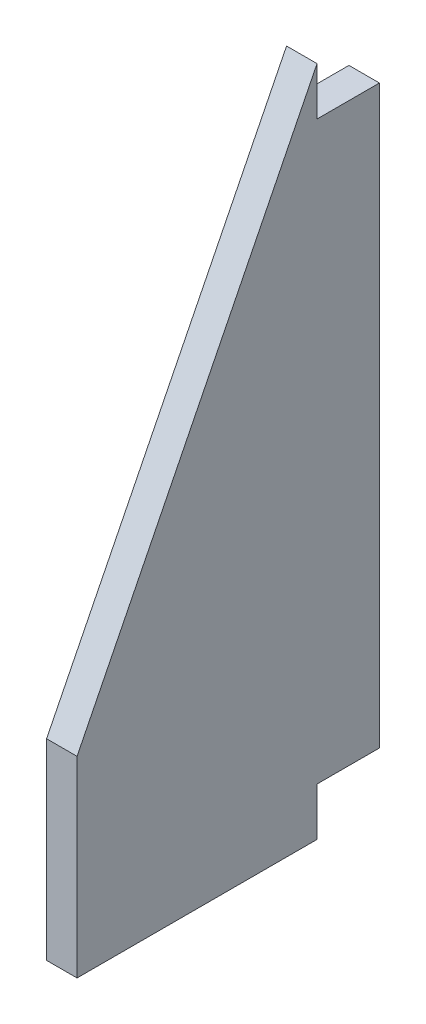
SolidWorks part; units mm, degrees
material "Beech"
ref_plane "Front Plane" through (0, 0, 0) normal (0, 0, 1) x (1, 0, 0)
ref_plane "Top Plane" through (0, 0, 0) normal (0, 1, 0) x (1, 0, 0)
ref_plane "Right Plane" through (0, 0, 0) normal (1, 0, 0) x (0, 0, -1)
sketch "Sketch1" plane through (0, 0, 0) normal (1, 0, 0) x (0, 0, -1)
  line L0 (-34, 0) -> (-84, 0)
  line L1 (-84, 0) -> (-84, 40)
  line L2 (-84, 40) -> (-34, 140)
  line L3 (-34, 140) -> (-34, 130)
  line L4 (-34, 10) -> (-21, 10)
  line L5 (-21, 10) -> (-21, 130)
  line L6 (-21, 130) -> (-34, 130)
  line L7 (-34, 10) -> (-34, 0)
  dimension "D1" = 50
  dimension "D2" = 100
  dimension "D3" = 140
  dimension "D4" = 34
  dimension "D5" = 21
  dimension "D6" = 10
  dimension "D7" = 10
extrude "Boss-Extrude1" add sketch "Sketch1" along normal mid plane 6.35
